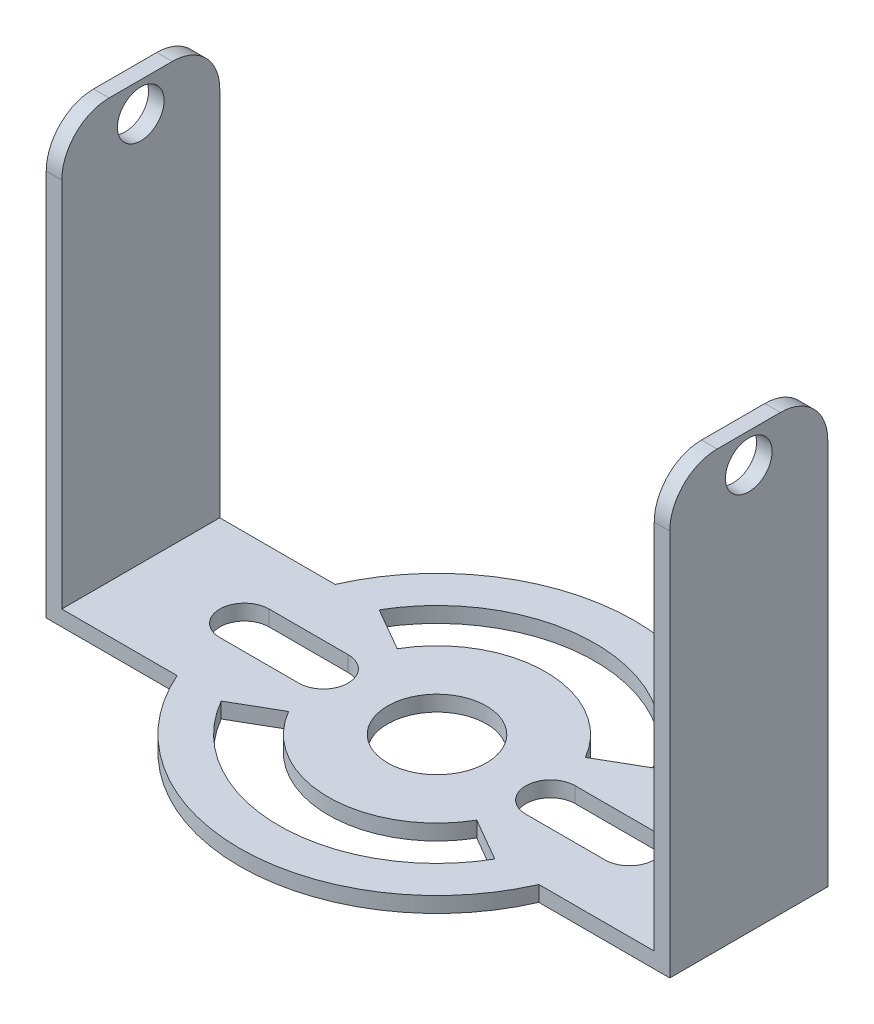
SolidWorks part; units mm, degrees
ref_plane "Front Plane" through (0, 0, 0) normal (0, 0, 1) x (1, 0, 0)
ref_plane "Top Plane" through (0, 0, 0) normal (0, 1, 0) x (1, 0, 0)
ref_plane "Right Plane" through (0, 0, 0) normal (1, 0, 0) x (0, 0, -1)
sketch "Sketch1" plane through (0, 0, 0) normal (0, 1, 0) x (1, 0, 0)
  line L6 (11.629, 5.08) -> (19.05, 5.08)
  line L7 (-19.05, -5.08) -> (-11.629, -5.08)
  line L10 (8.7988, 5.08) -> (6.0492, 3.4925)
  line L11 (-19.05, -5.08) -> (-19.05, 5.08)
  line L14 (-19.05, 0) -> (19.05, 0) construction
  line L15 (-19.05, 5.08) -> (-11.629, 5.08)
  line L16 (19.05, -5.08) -> (19.05, 5.08)
  line L17 (-19.05, -5.08) -> (19.05, 5.08) construction
  line L18 (-19.05, 5.08) -> (19.05, -5.08) construction
  line L19 (11.629, -5.08) -> (19.05, -5.08)
  line L20 (0, -12.6902) -> (0, 12.6902) construction
  line L21 (8.7988, -5.08) -> (6.0492, -3.4925)
  line L22 (12.3825, -1.5875) -> (7.3025, -1.5875)
  line L23 (-8.7988, -5.08) -> (-6.0492, -3.4925)
  line L24 (-8.7988, 5.08) -> (-6.0492, 3.4925)
  line L25 (-9.8425, 0) -> (-9.8425, 1.7673) construction
  line L26 (-7.3025, 1.5875) -> (-12.3825, 1.5875)
  line L27 (-12.3825, -1.5875) -> (-7.3025, -1.5875)
  line L28 (7.3025, 1.5875) -> (12.3825, 1.5875)
  circle A2 centre (0, 0) radius 3.175
  arc A8 (-11.629, -5.08) -> (11.629, -5.08) centre (0, 0) ccw
  arc A9 (11.629, 5.08) -> (-11.629, 5.08) centre (0, 0) ccw
  arc A12 (6.0492, 3.4925) -> (-6.0492, 3.4925) centre (0, -0.0038) ccw
  arc A13 (8.7988, 5.08) -> (-8.7988, 5.08) centre (0, -0.0038) ccw
  arc A14 (-6.0492, -3.4925) -> (6.0492, -3.4925) centre (0, -0.0038) ccw
  arc A15 (-8.7988, -5.08) -> (8.7988, -5.08) centre (0, -0.0038) ccw
  arc A16 (-12.3825, 1.5875) -> (-12.3825, -1.5875) centre (-12.3825, 0) ccw
  arc A17 (-7.3025, 1.5875) -> (-7.3025, -1.5875) centre (-7.3025, 0) cw
  arc A18 (12.3825, 1.5875) -> (12.3825, -1.5875) centre (12.3825, 0) cw
  arc A19 (7.3025, 1.5875) -> (7.3025, -1.5875) centre (7.3025, 0) ccw
  point P24 (0, 0)
  dimension "D3" = 6.35
  dimension "D1" = 38.1
  dimension "D2" = 10.16
  dimension "D7" = 1.5875
extrude "Boss-Extrude1" add sketch "Sketch1" along normal blind 1
sketch "Sketch2" plane through (19.05, 0, -13.97) normal (1, 0, 0) x (0, 0, -1)
  line L0 (-19.05, 1) -> (-19.05, 0) construction
  line L1 (-19.05, 0) -> (-8.89, 0)
  line L2 (-19.05, 0) -> (-19.05, 24.892)
  line L3 (-16.002, 27.94) -> (-11.938, 27.94)
  line L4 (-8.89, 0) -> (-8.89, 24.892)
  arc A0 (-11.938, 27.94) -> (-8.89, 24.892) centre (-11.938, 24.892) cw
  arc A1 (-19.05, 24.892) -> (-16.002, 27.94) centre (-16.002, 24.892) cw
  point P7 (-8.89, 27.94)
  point P10 (-19.05, 27.94)
  dimension "D3" = 3.048
  dimension "D1" = 10.16
  dimension "D2" = 27.94
  dimension "D4" = 0
extrude "Boss-Extrude2" add sketch "Sketch2" along normal blind 1
sketch "Sketch3" plane through (-19.05, 0, 13.97) normal (-1, 0, 0) x (0, 0, 1)
  line L0 (-19.05, 1) -> (-19.05, 0) construction
  line L1 (-8.89, 0) -> (-19.05, 0)
  line L2 (-8.89, 0) -> (-8.89, 24.892)
  line L3 (-11.938, 27.94) -> (-16.002, 27.94)
  line L4 (-19.05, 0) -> (-19.05, 24.892)
  arc A0 (-8.89, 24.892) -> (-11.938, 27.94) centre (-11.938, 24.892) ccw
  arc A1 (-16.002, 27.94) -> (-19.05, 24.892) centre (-16.002, 24.892) ccw
  point P8 (-8.89, 27.94)
  point P11 (-19.05, 27.94)
  dimension "D3" = 3.048
  dimension "D1" = 10.16
  dimension "D2" = 27.94
  dimension "D4" = 0
extrude "Boss-Extrude3" add sketch "Sketch3" along normal blind 1
sketch "Sketch4" plane through (-20.05, 0, 0) normal (-1, 0, 0) x (0, 0, 1)
  line L0 (2.032, 27.94) -> (-2.032, 27.94) construction
  line L1 (0, 0) -> (0, 27.94) construction
  circle A0 centre (0, 26.035) radius 1.5
  point P7 (0, 0)
  point P8 (0, 26.035)
  dimension "D1" = 3
  dimension "D2" = 1.905
extrude "Cut-Extrude1" cut sketch "Sketch4" against normal through all
